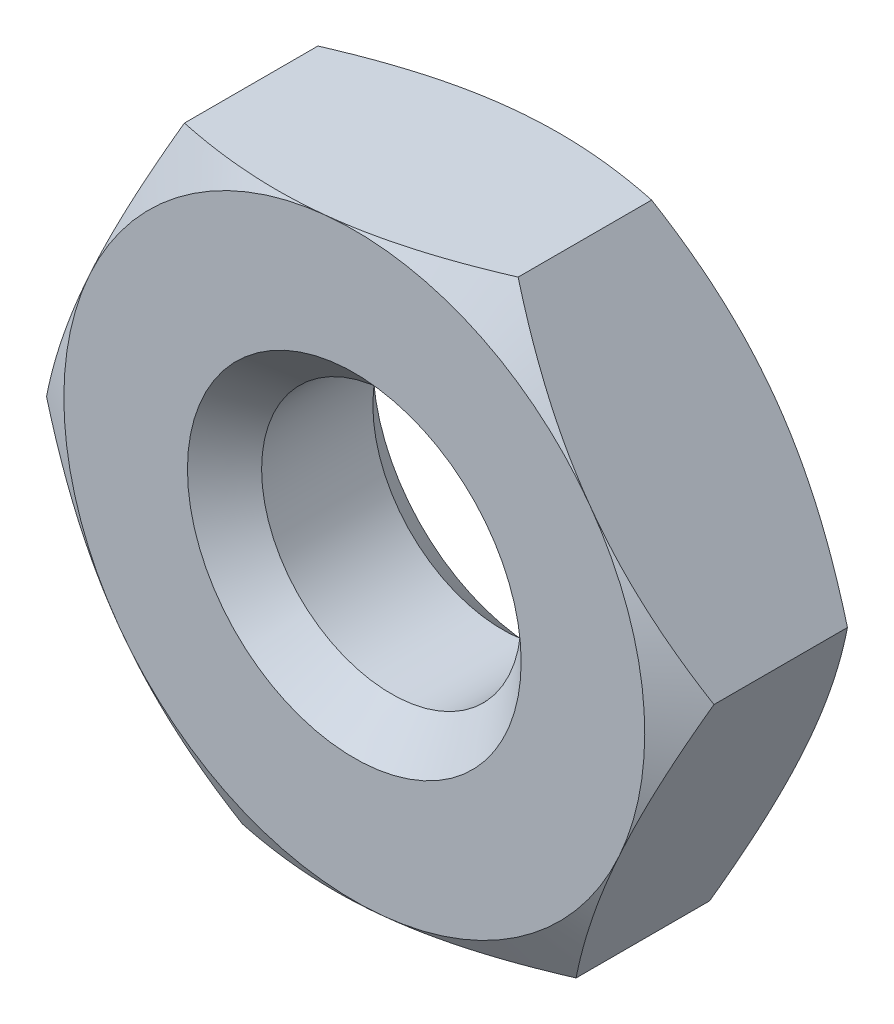
SolidWorks part; units mm, degrees
ref_plane "Přední rovina" through (0, 0, 0) normal (0, 0, 1) x (1, 0, 0)
ref_plane "Horní rovina" through (0, 0, 0) normal (0, 1, 0) x (1, 0, 0)
ref_plane "Pravá rovina" through (0, 0, 0) normal (1, 0, 0) x (0, 0, -1)
sketch "Skica1" plane through (0, 0, 0) normal (0, 0, 1) x (1, 0, 0)
  line L1 (1.1155, 2.4737) -> (-1.5845, 2.2029)
  line L2 (-1.5845, 2.2029) -> (-2.7, -0.2708)
  line L3 (-2.7, -0.2708) -> (-1.1155, -2.4737)
  line L4 (-1.1155, -2.4737) -> (1.5845, -2.2029)
  line L5 (1.5845, -2.2029) -> (2.7, 0.2708)
  line L6 (2.7, 0.2708) -> (1.1155, 2.4737)
  circle A0 centre (0, 0) radius 1.05
  circle A1 centre (0, 0) radius 2.35 construction
  dimension "D3" = 2.1
  dimension "D1" = 2.7
  dimension "D2" = 4.7
extrude "Přidat vysunutím1" add sketch "Skica1" along normal blind 1.5
ref_plane "Rovina1" through (0, 0, 0) normal (0.4111, 0.9116, 0) x (0.9116, -0.4111, 0)
sketch "Skica2" plane through (0, 0, 0) normal (0.4111, 0.9116, 0) x (0.9116, -0.4111, 0)
  line L0 (-2.35, -1.5) -> (-2.35, 0) construction
  line L1 (-2.35, -1.5) -> (-2.35, 0)
  line L2 (-2.35, 0) -> (-3.649, 0)
  line L3 (-3.649, 0) -> (-3.649, -1.5)
  line L4 (-3.649, -1.5) -> (-2.35, -1.5)
  line L5 (-2.35, -1.5) -> (-3.649, -0.75)
  line L6 (-3.649, -0.75) -> (-2.35, 0)
  line L7 (0, -0.75) -> (0, -3.1595) construction
  dimension "D1" = 30
revolve "Odebrat rotací1" cut sketch "Skica2" angle 360 about L7
chamfer "Zkosení1" distance 0.3 angle 45 2 edges at (1.05, 0, 0) (1.05, 0, 1.5)
